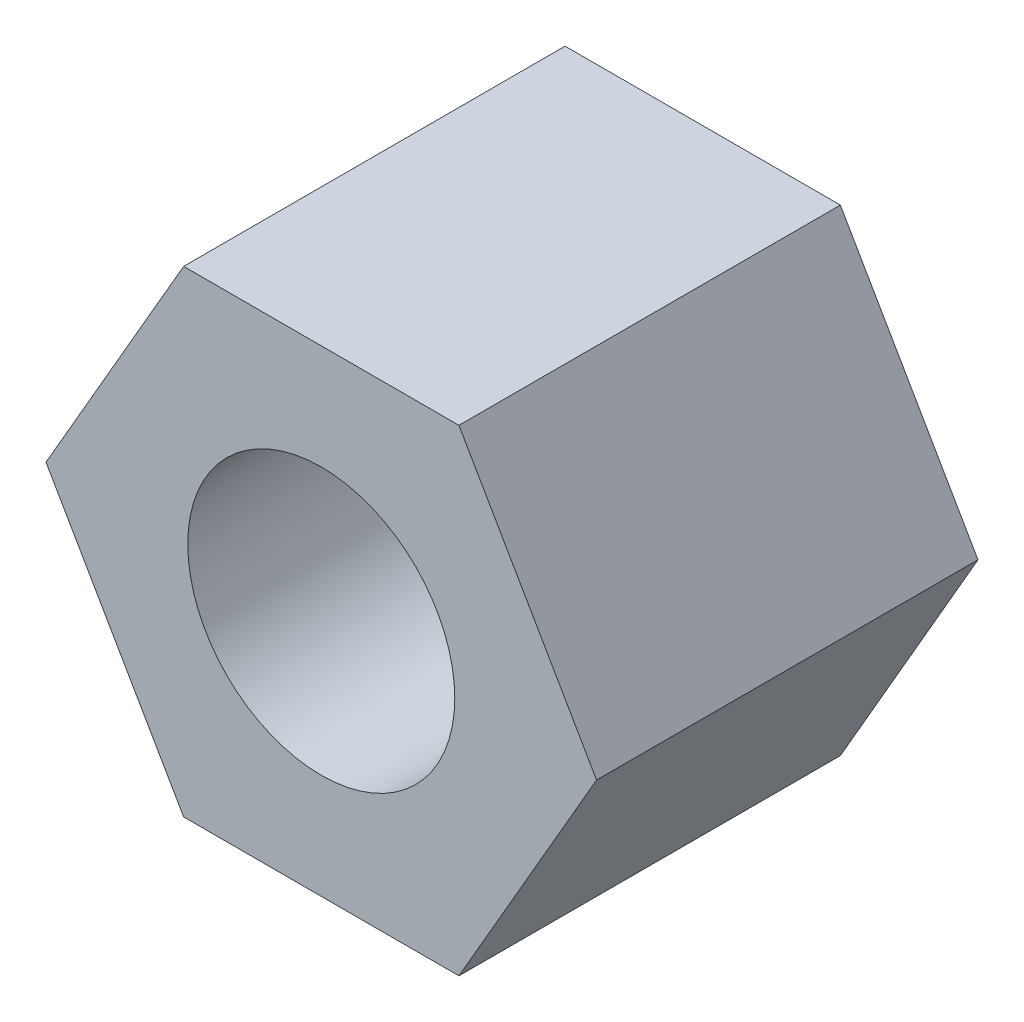
SolidWorks part; units mm, degrees
ref_plane "Alzado" through (0, 0, 0) normal (0, 0, 1) x (1, 0, 0)
ref_plane "Planta" through (0, 0, 0) normal (0, 1, 0) x (1, 0, 0)
ref_plane "Vista lateral" through (0, 0, 0) normal (1, 0, 0) x (0, 0, -1)
sketch "Croquis1" plane through (0, 0, 0) normal (0, 0, 1) x (1, 0, 0)
  line L1 (2.8868, 0) -> (1.4434, 2.5)
  line L2 (1.4434, 2.5) -> (-1.4434, 2.5)
  line L3 (-1.4434, 2.5) -> (-2.8868, 0)
  line L4 (-2.8868, 0) -> (-1.4434, -2.5)
  line L5 (-1.4434, -2.5) -> (1.4434, -2.5)
  line L6 (1.4434, -2.5) -> (2.8868, 0)
  circle A0 centre (0, 0) radius 2.5 construction
  circle A1 centre (0, 0) radius 1.4
  point P10 (0, 0)
  point P11 (0, 0)
  dimension "D1" = 2.8
  dimension "D2" = 5
extrude "Saliente-Extruir1" add sketch "Croquis1" along normal blind 4
